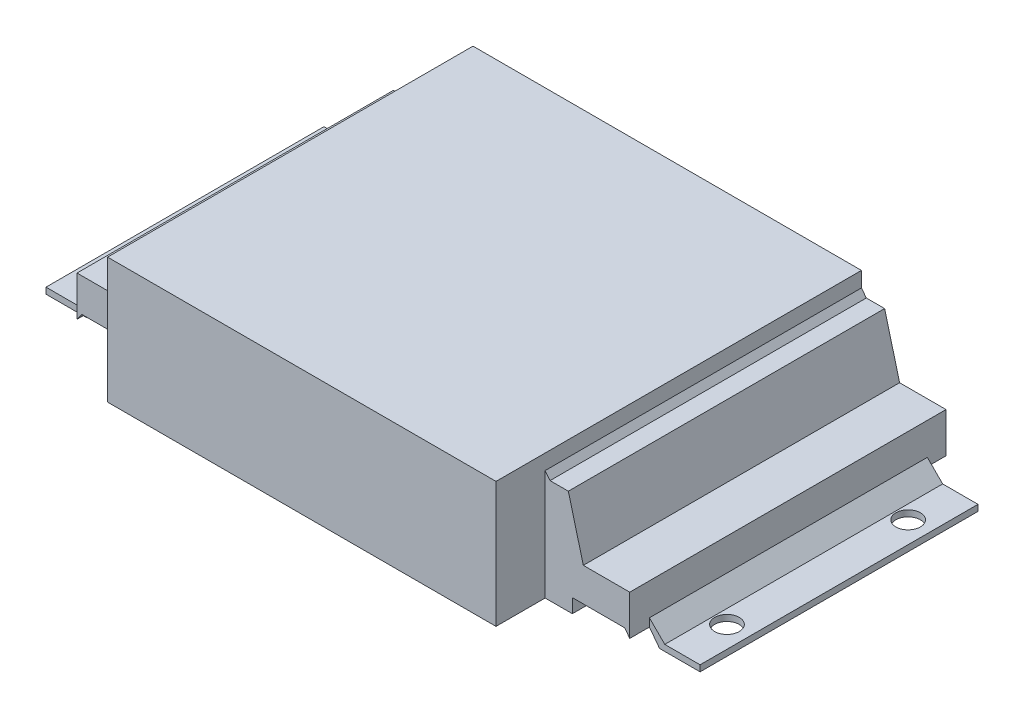
SolidWorks part; units mm, degrees
ref_plane "Front Plane" through (0, 0, 0) normal (0, 0, 1) x (1, 0, 0)
ref_plane "Top Plane" through (0, 0, 0) normal (0, 1, 0) x (1, 0, 0)
ref_plane "Right Plane" through (0, 0, 0) normal (1, 0, 0) x (0, 0, -1)
sketch "Sketch5" plane through (0, 0, 0) normal (0, 1, 0) x (1, 0, 0)
  line L5 (106.5, -59.5) -> (-106.5, -59.5) construction
  line L6 (106.5, -59.5) -> (106.5, 59.5) construction
  line L7 (106.5, 59.5) -> (-106.5, 59.5) construction
  line L8 (-106.5, -59.5) -> (-106.5, 59.5) construction
  line L9 (106.5, -59.5) -> (-106.5, 59.5) construction
  line L10 (106.5, 59.5) -> (-106.5, -59.5) construction
  point P0 (0, 0)
  dimension "D1" = 213
  dimension "D2" = 119
sketch "Sketch2" plane through (0, 0, 0) normal (0, 1, 0) x (1, 0, 0)
  line L0 (-252.0574, 6.7231) -> (309.2759, 6.7231) construction
  line L1 (-160.6007, -26.7969) -> (400.7327, -26.7969) construction
sketch "Sketch6" plane through (0, 0, 0) normal (0, 0, 1) x (1, 0, 0)
  line L0 (-142.4834, -10.6446) -> (348.85, -10.6446) construction
sketch "Sketch7" plane through (0, 0, 0) normal (0, 1, 0) x (1, 0, 0)
  line L0 (0, 53.4074) -> (0, -37.0926) construction
  line L1 (-106.5, -37.0926) -> (106.5, -37.0926)
  line L2 (-106.5, -37.0926) -> (-106.5, 53.4074)
  line L3 (-106.5, 53.4074) -> (106.5, 53.4074)
  line L4 (106.5, -37.0926) -> (106.5, 53.4074)
  point P0 (0, 0)
  dimension "D1" = 213
  dimension "D2" = 90.5
extrude "Boss-Extrude1" add sketch "Sketch7" along normal blind 2
sketch "Sketch8" plane through (0, 2, 0) normal (0, 1, 0) x (1, 0, 0)
  line L0 (106.5, 59.5) -> (-106.5, 59.5) construction
  line L1 (-90, 59.5) -> (90, 59.5)
  line L2 (-90, 59.5) -> (-90, -43.5)
  line L3 (-90, -43.5) -> (90, -43.5)
  line L4 (90, 59.5) -> (90, -43.5)
  line L5 (0, 59.5) -> (0, -43.5) construction
  line L6 (-64.0431, -43.5) -> (-64.0431, -59.5)
  line L7 (106.5, -59.5) -> (-106.5, -59.5) construction
  line L8 (-64.0431, -59.5) -> (62.4506, -59.5)
  line L9 (62.4506, -59.5) -> (62.4506, -43.5)
  line M7 (106.5, 53.4074) -> (-106.5, 53.4074)
  line M9 (-106.5, -37.0926) -> (106.5, -37.0926)
  dimension "D1" = 180
  dimension "D2" = 103
extrude "Boss-Extrude2" add sketch "Sketch8" along normal blind 40.9 contours L5 L2 M7 M9 | L5 L4 M7 M9 | L8 L9 L3 L6 | L5 L2 L3 M9 | L5 L3 L4 M9 | L5 L1 L2 M7
chamfer "Chamfer1" distance 5 angle 45 2 edges at (-90, 2, -8.1574) (90, 2, -8.1574)
sketch "Sketch9" plane through (0, 0, 59.5) normal (0, 0, 1) x (1, 0, 0)
  line L0 (-93.2917, 0) -> (-88.3678, 6.5547)
  line L1 (106.5, 0) -> (-106.5, 0) construction
  line L2 (-88.3678, 6.5547) -> (-71.3092, 6.5547)
  line L3 (-71.3092, 6.5547) -> (-71.3092, 1.1373)
  line L4 (-71.3092, 1.1373) -> (71.3092, 1.1373)
  line L9 (93.2917, -4.0123) -> (-93.2917, -4.0123)
  line L10 (-93.2917, -4.0123) -> (-93.2917, 0)
  line L11 (0, 1.1373) -> (0, -4.0123) construction
  line L12 (93.2917, -4.0123) -> (93.2917, 0)
  line L13 (71.3092, 6.5547) -> (71.3092, 1.1373)
  line L14 (88.3678, 6.5547) -> (71.3092, 6.5547)
  line L15 (93.2917, 0) -> (88.3678, 6.5547)
extrude "Cut-Extrude1" cut sketch "Sketch9" against normal through all contours L2 L3 L4 L13 L14 L15 L12 L9 L10 L0
sketch "Sketch10" plane through (0, 0, 59.5) normal (0, 0, 1) x (1, 0, 0)
  line L0 (-90, 17.4359) -> (-74.8812, 17.4359)
  line L1 (-90, 42.9) -> (-90, 4.3819) construction
  line L2 (-74.8812, 17.4359) -> (-70.0005, 35.9139)
  line L3 (-70.0005, 35.9139) -> (-64.0431, 35.9139)
  line L4 (-64.0431, 42.9) -> (-64.0431, 2) construction
  line L5 (-64.0431, 35.9139) -> (-58.5696, 42.9)
  line L6 (-64.0431, 42.9) -> (62.4506, 42.9) construction
  line L7 (-58.5696, 42.9) -> (58.5696, 42.9)
  line L8 (0, 42.9) -> (0, 0) construction
  line L10 (106.5, 0) -> (-106.5, 0) construction
  line L11 (-90, 0) -> (-90, 17.4359)
  line L12 (-90, 17.4359) -> (-90, 53.5591)
  line L13 (-90, 53.5591) -> (90, 53.5591)
  line L14 (90, 17.4359) -> (90, 53.5591)
  line L15 (90, 0) -> (90, 17.4359)
  line L16 (64.0431, 35.9139) -> (58.5696, 42.9)
  line L17 (70.0005, 35.9139) -> (64.0431, 35.9139)
  line L18 (74.8812, 17.4359) -> (70.0005, 35.9139)
  line L19 (90, 17.4359) -> (74.8812, 17.4359)
  point P19 (0, 53.5591)
  line M10 (62.4506, 2) -> (62.4506, 42.9)
  line M11 (62.4506, 42.9) -> (-64.0431, 42.9)
  line M12 (-64.0431, 42.9) -> (-64.0431, 2)
extrude "Cut-Extrude2" cut sketch "Sketch10" against normal through all contours L19 L14 L13 L12 L0 L2 L3 L7 L16 L17 L18 M12 M11 M10
sketch "Sketch11" plane through (0, 2, 0) normal (0, 1, 0) x (1, 0, 0)
  line L0 (-106.5, 8.1574) -> (106.5, 8.1574) construction
  line L1 (-106.5, 53.4074) -> (-106.5, -37.0926) construction
  line L2 (106.5, -37.0926) -> (106.5, 53.4074) construction
  circle A0 centre (99.5, 37.6574) radius 4
  circle A1 centre (-99.5, 37.6574) radius 4
  circle A2 centre (-99.5, -21.3426) radius 4
  circle A3 centre (99.5, -21.3426) radius 4
  dimension "D1" = 8
  dimension "D2" = 199
  dimension "D3" = 99.5
  dimension "D4" = 59
extrude "Cut-Extrude3" cut sketch "Sketch11" against normal blind 40.9
